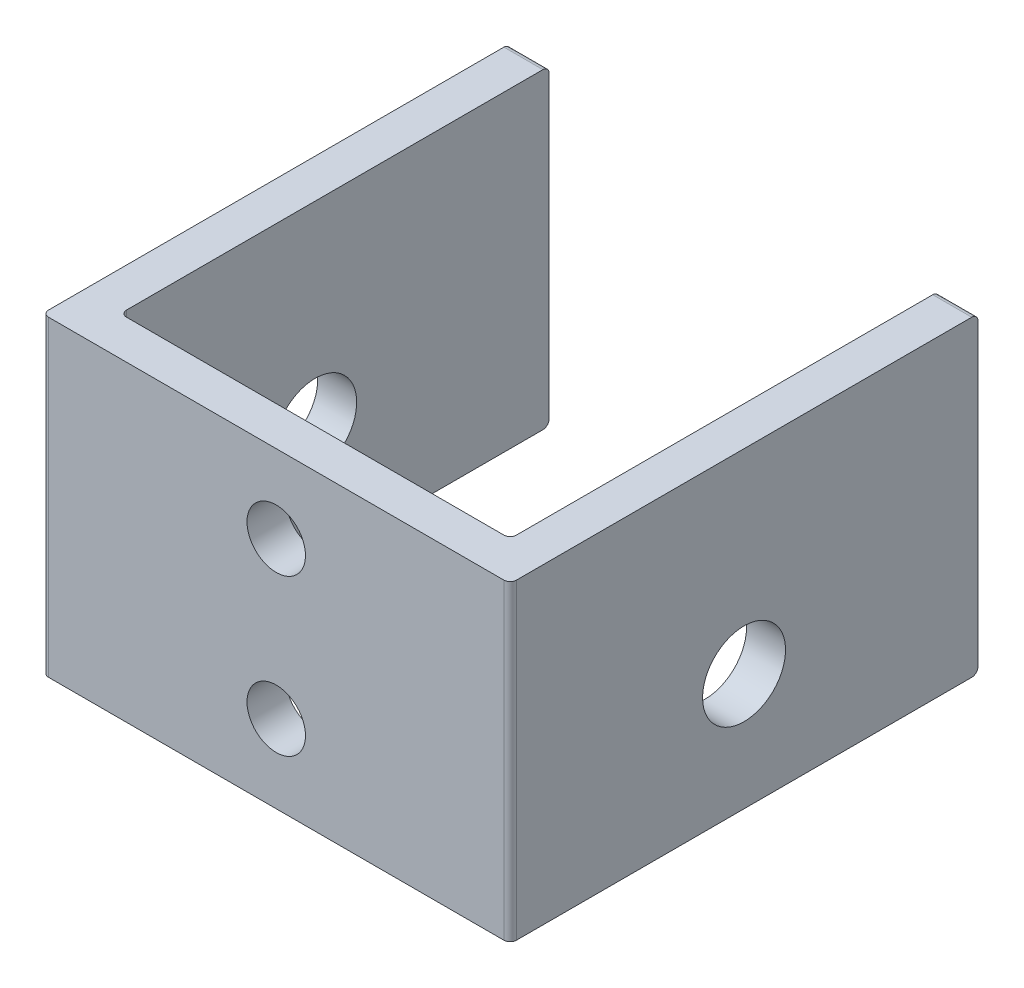
SolidWorks part; units mm, degrees
ref_plane "Front" through (0, 0, 0) normal (0, 0, 1) x (1, 0, 0)
ref_plane "Top" through (0, 0, 0) normal (0, 1, 0) x (1, 0, 0)
ref_plane "Right" through (0, 0, 0) normal (1, 0, 0) x (0, 0, -1)
sketch "Sketch1" plane through (0, 0, 0) normal (0, 1, 0) x (1, 0, 0)
  line L0 (-15.875, 19.05) -> (-15.875, -15.875)
  line L2 (-19.05, 19.05) -> (-19.05, -19.05)
  line L3 (-19.05, -19.05) -> (19.05, -19.05)
  line L4 (19.05, 19.05) -> (19.05, -19.05)
  line L5 (-19.05, 19.05) -> (19.05, -19.05) construction
  line L6 (-19.05, -19.05) -> (19.05, 19.05) construction
  line L7 (-15.875, -15.875) -> (15.875, -15.875)
  line L8 (15.875, 19.05) -> (15.875, -15.875)
  line L9 (-19.05, 19.05) -> (-15.875, 19.05)
  line L10 (19.05, 19.05) -> (15.875, 19.05)
  point P0 (0, 0)
  dimension "D1" = 38.1
  dimension "D3" = 38.1
  dimension "D2" = 31.75
extrude "Boss-Extrude1" add sketch "Sketch1" along normal blind 25.4
hole_wizard "1/4 Clearance Hole1" positions "Sketch2" profile "Sketch3" hole size "1/4" standard "ANSI Inch" end condition through all
sketch "Sketch2" plane through (-19.05, 0, 0) normal (1, 0, 0) x (0, 0, -1)
  line L2 (0, 12.7) -> (0, 9.525)
  line L3 (-19.05, 25.4) -> (19.05, 0)
  line L4 (19.05, 25.4) -> (19.05, 0) construction
  line L8 (-0.0025, 9.525) -> (0, 9.525)
  line L9 (19.05, 25.4) -> (19.05, 0) construction
  line L10 (19.05, 0) -> (-19.05, 0) construction
  point P33 (-0.0025, 9.525)
  dimension "D1" = 3.175
  dimension "D2" = 0.0025
  dimension "D3" = 19.0525
  dimension "D4" = 9.525
sketch "Sketch3" plane through (-19.05, 9.525, 0.0025) normal (0, 1, 0) x (0, 0, 1)
  line L0 (0, 0) -> (0, 38.1)
  line L1 (0, 38.1) -> (3.3782, 38.1)
  line L2 (3.3782, 38.1) -> (3.3782, 0)
  line L5 (3.3782, 0) -> (0, 0)
  line L11 (0, -6.35) -> (0, 107.95) construction
  dimension "Thru Hole Dia." = 6.7564
  dimension "Thru Hole Depth" = 38.1
hole_wizard "3/16 (0.1875) Diameter Hole1" positions "Sketch5" profile "Sketch7" hole size "3/16" standard "ANSI Inch" end condition through all
sketch "Sketch5" plane through (0, 0, 15.875) normal (0, 0, -1) x (-1, 0, 0)
  line L0 (0, 0) -> (0, 6.35)
  line L1 (0, 6.35) -> (0, 19.05)
  line L2 (0, 19.05) -> (0, 25.4)
  line L3 (-15.875, 25.4) -> (15.875, 25.4) construction
  point P0 (0, 6.35)
  point P2 (0, 19.05)
  dimension "D1" = 12.7
sketch "Sketch7" plane through (0, 6.35, 15.875) normal (1, 0, 0) x (0, 1, 0)
  line L0 (0, 0) -> (0, 3.175)
  line L1 (0, 3.175) -> (2.3812, 3.175)
  line L2 (2.3812, 3.175) -> (2.3812, 0)
  line L5 (2.3812, 0) -> (0, 0)
  line L11 (0, -6.35) -> (0, 107.95) construction
  dimension "Thru Hole Dia." = 4.7625
  dimension "Thru Hole Depth" = 3.175
fillet "Fillet1" radius 0.508 8 edges at (-15.875, 12.7, 15.875) (15.875, 12.7, 15.875) (17.4625, 0, -19.05) (17.4625, 25.4, -19.05) (-17.4625, 25.4, -19.05) (-17.4625, 0, -19.05) (19.05, 12.7, 19.05) (-19.05, 12.7, 19.05)
